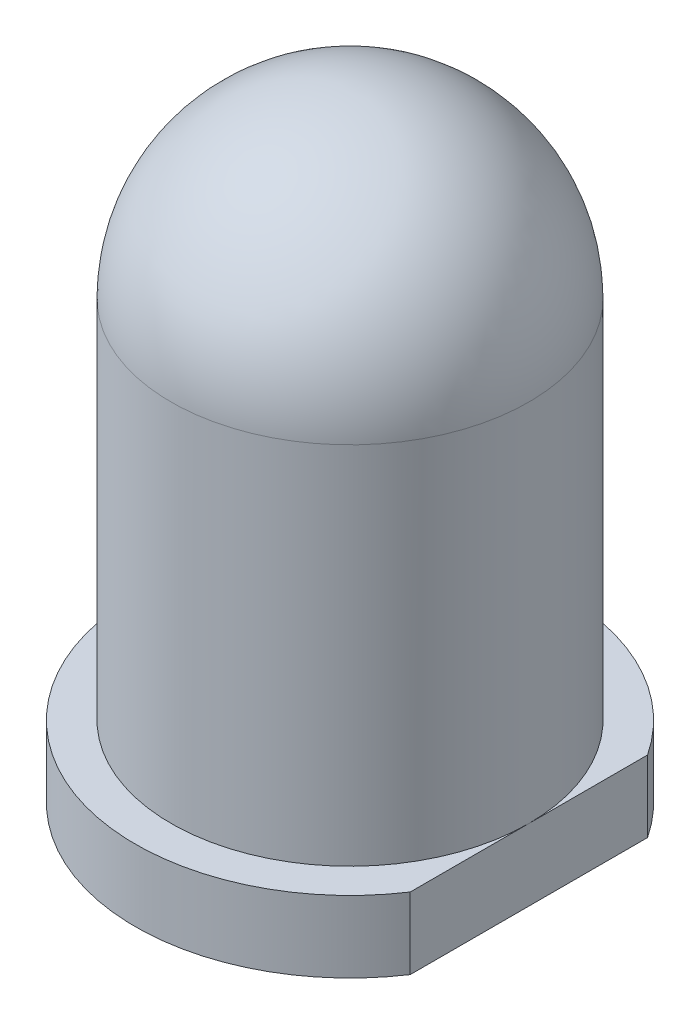
SolidWorks part; units mm, degrees
ref_plane "Front Plane" through (0, 0, 0) normal (0, 0, 1) x (1, 0, 0)
ref_plane "Top Plane" through (0, 0, 0) normal (0, 1, 0) x (1, 0, 0)
ref_plane "Right Plane" through (0, 0, 0) normal (1, 0, 0) x (0, 0, -1)
sketch "Sketch1" plane through (0, 0, 0) normal (0, 1, 0) x (1, 0, 0)
  circle A0 centre (0, 0) radius 2.5
  dimension "D1" = 5
extrude "Boss-Extrude1" add sketch "Sketch1" along normal blind 8.6
sketch "Sketch2" plane through (0, 0, 0) normal (0, -1, 0) x (1, 0, 0)
  circle A0 centre (0, 0) radius 3
  dimension "D1" = 6
extrude "Boss-Extrude2" add sketch "Sketch2" against normal blind 1
sketch "Sketch3" plane through (0, 0, 0) normal (0, -1, 0) x (1, 0, 0)
  line L1 (4.0879, -2.9781) -> (2.5, -2.9781)
  line L2 (4.0879, -2.9781) -> (4.0879, 3.2361)
  line L3 (4.0879, 3.2361) -> (2.5, 3.2361)
  line L4 (2.5, -2.9781) -> (2.5, 3.2361)
  circle A1 centre (0, 0) radius 2.5 construction
extrude "Cut-Extrude1" cut sketch "Sketch3" against normal through all
fillet "Fillet1" radius 2.5 1 edges at (0, 8.6, 2.5)
